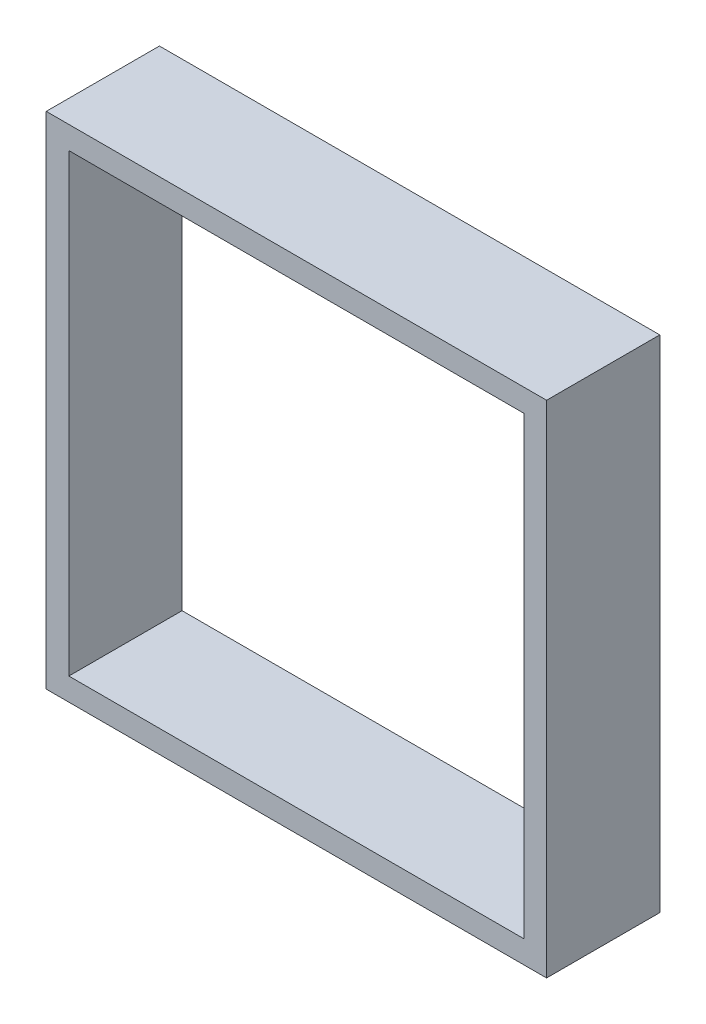
SolidWorks part; units mm, degrees
ref_plane "前视基准面" through (0, 0, 0) normal (0, 0, 1) x (1, 0, 0)
ref_plane "上视基准面" through (0, 0, 0) normal (0, 1, 0) x (1, 0, 0)
ref_plane "右视基准面" through (0, 0, 0) normal (1, 0, 0) x (0, 0, -1)
sketch "草图1" plane through (0, 0, 0) normal (0, 0, 1) x (1, 0, 0)
  line L1 (-47.2727, 13.7455) -> (-3.0727, 13.7455)
  line L2 (-47.2727, 13.7455) -> (-47.2727, -30.4545)
  line L3 (-47.2727, -30.4545) -> (-3.0727, -30.4545)
  line L4 (-3.0727, 13.7455) -> (-3.0727, -30.4545)
  line L5 (-45.2727, 11.7455) -> (-5.0727, 11.7455)
  line L6 (-45.2727, 11.7455) -> (-45.2727, -28.4545)
  line L7 (-45.2727, -28.4545) -> (-5.0727, -28.4545)
  line L8 (-5.0727, 11.7455) -> (-5.0727, -28.4545)
  dimension "D1" = 2
  dimension "D2" = 2
  dimension "D3" = 2
  dimension "D4" = 2
  dimension "D5" = 40.2
  dimension "D6" = 40.2
extrude "凸台-拉伸1" add sketch "草图1" along normal blind 10
